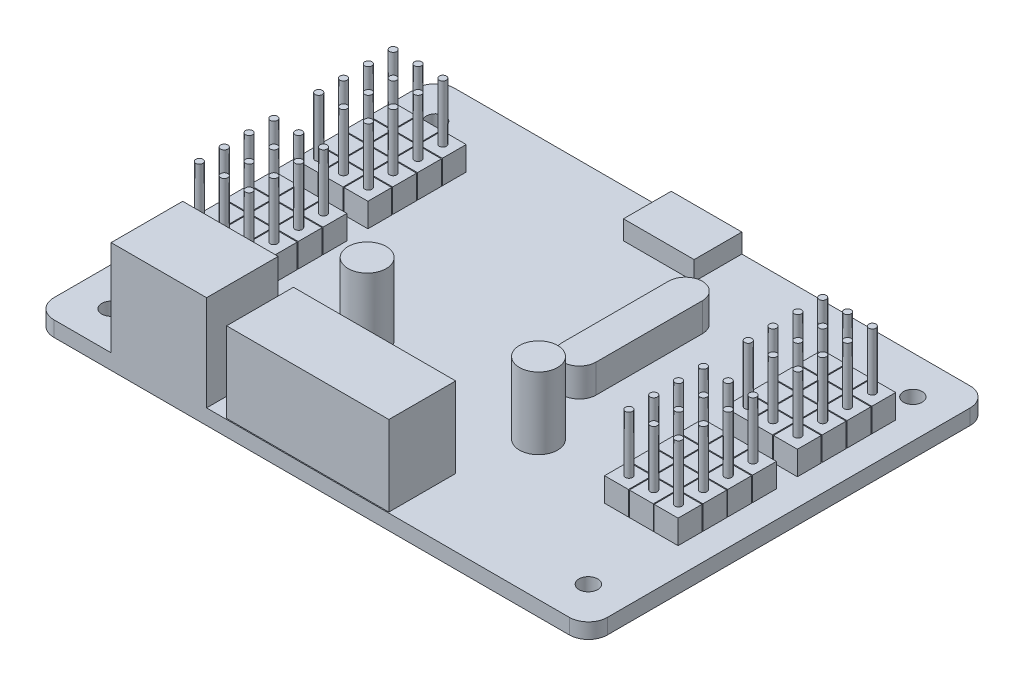
SolidWorks part; units mm, degrees
ref_plane "前视基准面" through (0, 0, 0) normal (0, 0, 1) x (1, 0, 0)
ref_plane "上视基准面" through (0, 0, 0) normal (0, 1, 0) x (1, 0, 0)
ref_plane "右视基准面" through (0, 0, 0) normal (1, 0, 0) x (0, 0, -1)
sketch "草图1" plane through (0, 0, 0) normal (0, 1, 0) x (1, 0, 0)
  line L1 (0, 0) -> (58, 0)
  line L2 (0, 0) -> (0, 42)
  line L3 (0, 42) -> (58, 42)
  line L4 (58, 0) -> (58, 42)
  dimension "D1" = 58
  dimension "D2" = 42
extrude "凸台-拉伸1" add sketch "草图1" along normal blind 1.6
sketch "草图2" plane through (0, 1.6, 0) normal (0, 1, 0) x (1, 0, 0)
  line L0 (0, 0) -> (58, 0) construction
  line L1 (8, 0) -> (18, 0)
  line L2 (8, 0) -> (8, 7.5)
  line L3 (8, 7.5) -> (18, 7.5)
  line L4 (18, 0) -> (18, 7.5)
  line L5 (0, 42) -> (0, 0) construction
  dimension "D1" = 10
  dimension "D2" = 7.5
  dimension "D3" = 18
extrude "凸台-拉伸2" add sketch "草图2" along normal blind 10
sketch "草图4" plane through (0, 1.6, 0) normal (0, 1, 0) x (1, 0, 0)
  line L0 (18, 0) -> (58, 0) construction
  line L1 (20, 0.1) -> (37, 0.1)
  line L2 (20, 0.1) -> (20, 7.1)
  line L3 (20, 7.1) -> (37, 7.1)
  line L4 (37, 0.1) -> (37, 7.1)
  line L5 (58, 0) -> (58, 42) construction
  dimension "D1" = 0.1
  dimension "D2" = 17
  dimension "D3" = 38
  dimension "D4" = 7
extrude "凸台-拉伸3" add sketch "草图4" along normal blind 8.4
sketch "草图5" plane through (0, 1.6, 0) normal (0, 1, 0) x (1, 0, 0)
  line L0 (0, 42) -> (0, 0) construction
  line L1 (58, 42) -> (0, 42) construction
  line L2 (29, 42) -> (29, -6.1347) construction
  line L3 (0, 21) -> (65.4073, 21) construction
  circle A0 centre (4, 38) radius 0.9782
  circle A1 centre (54, 38) radius 0.9782
  circle A2 centre (54, 4) radius 0.9782
  circle A3 centre (4, 4) radius 0.9782
  dimension "D1" = 4
  dimension "D2" = 4
extrude "切除-拉伸1" cut sketch "草图5" against normal through all
fillet "圆角1" radius 2 4 edges at (58, 0.8, 0) (0, 0.8, 0) (0, 0.8, -42) (58, 0.8, -42)
sketch "草图6" plane through (0, 1.6, 0) normal (0, 1, 0) x (1, 0, 0)
  line L5 (56, 42) -> (2, 42) construction
  line L6 (24.6802, 37) -> (32.0802, 37)
  line L7 (24.6802, 37) -> (24.6802, 42)
  line L8 (24.6802, 42) -> (32.0802, 42)
  line L9 (32.0802, 37) -> (32.0802, 42)
  line L10 (24.6802, 37) -> (32.0802, 42) construction
  line L11 (24.6802, 42) -> (32.0802, 37) construction
  point P0 (28.3802, 39.5)
  dimension "D1" = 7.4
  dimension "D2" = 5
extrude "凸台-拉伸4" add sketch "草图6" along normal blind 2
sketch "草图7" plane through (0, 1.6, 0) normal (0, 1, 0) x (1, 0, 0)
  line L0 (0, 40) -> (0, 2) construction
  line L1 (2.5, 35) -> (5, 35)
  line L2 (2.5, 35) -> (2.5, 32.5)
  line L3 (2.5, 32.5) -> (5, 32.5)
  line L4 (5, 35) -> (5, 32.5)
  line L5 (5.1, 35) -> (7.6, 35)
  line L6 (7.6, 35) -> (7.6, 32.5)
  line L7 (5.1, 32.5) -> (7.6, 32.5)
  line L8 (5.1, 35) -> (5.1, 32.5)
  line L9 (7.7, 35) -> (10.2, 35)
  line L10 (10.2, 35) -> (10.2, 32.5)
  line L11 (7.7, 32.5) -> (10.2, 32.5)
  line L12 (7.7, 35) -> (7.7, 32.5)
  line L13 (5.1, 32.4) -> (7.6, 32.4)
  line L14 (7.6, 32.4) -> (7.6, 29.9)
  line L15 (5.1, 29.9) -> (7.6, 29.9)
  line L16 (5.1, 32.4) -> (5.1, 29.9)
  line L17 (7.7, 32.4) -> (10.2, 32.4)
  line L18 (10.2, 32.4) -> (10.2, 29.9)
  line L19 (7.7, 29.9) -> (10.2, 29.9)
  line L20 (7.7, 32.4) -> (7.7, 29.9)
  line L21 (5.1, 29.8) -> (7.6, 29.8)
  line L22 (7.6, 29.8) -> (7.6, 27.3)
  line L23 (5.1, 27.3) -> (7.6, 27.3)
  line L24 (5.1, 29.8) -> (5.1, 27.3)
  line L25 (7.7, 29.8) -> (10.2, 29.8)
  line L26 (10.2, 29.8) -> (10.2, 27.3)
  line L27 (7.7, 27.3) -> (10.2, 27.3)
  line L28 (7.7, 29.8) -> (7.7, 27.3)
  line L29 (5.1, 27.2) -> (7.6, 27.2)
  line L30 (7.6, 27.2) -> (7.6, 24.7)
  line L31 (5.1, 24.7) -> (7.6, 24.7)
  line L32 (5.1, 27.2) -> (5.1, 24.7)
  line L33 (7.7, 27.2) -> (10.2, 27.2)
  line L34 (10.2, 27.2) -> (10.2, 24.7)
  line L35 (7.7, 24.7) -> (10.2, 24.7)
  line L36 (7.7, 27.2) -> (7.7, 24.7)
  line L37 (2.5, 32.4) -> (5, 32.4)
  line L38 (5, 32.4) -> (5, 29.9)
  line L39 (2.5, 29.9) -> (5, 29.9)
  line L40 (2.5, 32.4) -> (2.5, 29.9)
  line L41 (2.5, 29.8) -> (5, 29.8)
  line L42 (5, 29.8) -> (5, 27.3)
  line L43 (2.5, 27.3) -> (5, 27.3)
  line L44 (2.5, 29.8) -> (2.5, 27.3)
  line L45 (2.5, 27.2) -> (5, 27.2)
  line L46 (5, 27.2) -> (5, 24.7)
  line L47 (2.5, 24.7) -> (5, 24.7)
  line L48 (2.5, 27.2) -> (2.5, 24.7)
  circle A0 centre (4, 38) radius 0.9782 construction
  dimension "D1" = 2.5
  dimension "D2" = 2.5
  dimension "D3" = 3
  dimension "D4" = 3
  dimension "D5" = 4
extrude "凸台-拉伸5" add sketch "草图7" along normal blind 2.5
pattern_linear "阵列(线性)1" count 2 spacing 45 along (1, 0, 0) count 2 spacing 12.5 along (0, 0, 1) of "凸台-拉伸5"
sketch "草图8" plane through (0, 4.1, 0) normal (0, 1, 0) x (1, 0, 0)
  circle A0 centre (3.75, 33.802) radius 0.375
  circle A1 centre (6.35, 33.802) radius 0.375
  circle A2 centre (8.95, 33.802) radius 0.375
  circle A3 centre (6.35, 31.202) radius 0.375
  circle A4 centre (8.95, 31.202) radius 0.375
  circle A5 centre (6.35, 28.602) radius 0.375
  circle A6 centre (8.95, 28.602) radius 0.375
  circle A7 centre (6.35, 26.002) radius 0.375
  circle A8 centre (8.95, 26.002) radius 0.375
  circle A9 centre (3.75, 31.202) radius 0.375
  circle A10 centre (3.75, 28.602) radius 0.375
  circle A11 centre (3.75, 26.002) radius 0.375
  dimension "D1" = 0.75
  dimension "D2" = 3
  dimension "D3" = 4
extrude "凸台-拉伸6" add sketch "草图8" along normal blind 6
pattern_linear "阵列(线性)2" count 2 spacing 45 along (1, 0, 0) count 2 spacing 12.5 along (0, 0, 1) of "凸台-拉伸6"
sketch "草图9" plane through (0, 1.6, 0) normal (0, 1, 0) x (1, 0, 0)
  circle A0 centre (20.268, 14.5579) radius 2
  circle A1 centre (38.2205, 14.5579) radius 2
  dimension "D1" = 4
extrude "凸台-拉伸7" add sketch "草图9" along normal blind 7.5
sketch "草图10" plane through (0, 1.6, 0) normal (0, 1, 0) x (1, 0, 0)
  line L0 (35.4726, 21.5801) -> (35.4726, 32.6935) construction
  line L1 (33.7018, 21.5801) -> (33.7018, 32.6935)
  line L2 (37.2435, 21.5801) -> (37.2435, 32.6935)
  arc A0 (33.7018, 21.5801) -> (37.2435, 21.5801) centre (35.4726, 21.5801) ccw
  arc A1 (37.2435, 32.6935) -> (33.7018, 32.6935) centre (35.4726, 32.6935) ccw
  point P2 (35.4726, 27.1368)
extrude "凸台-拉伸8" add sketch "草图10" along normal blind 3
sketch "草图11" plane through (0, 0, 0) normal (0, -1, 0) x (1, 0, 0)
  line L1 (6.4357, -5.4688) -> (51.2712, -5.4688)
  line L2 (6.4357, -5.4688) -> (6.4357, -34.773)
  line L3 (6.4357, -34.773) -> (51.2712, -34.773)
  line L4 (51.2712, -5.4688) -> (51.2712, -34.773)
extrude "凸台-拉伸9" add sketch "草图11" along normal blind 1.6
